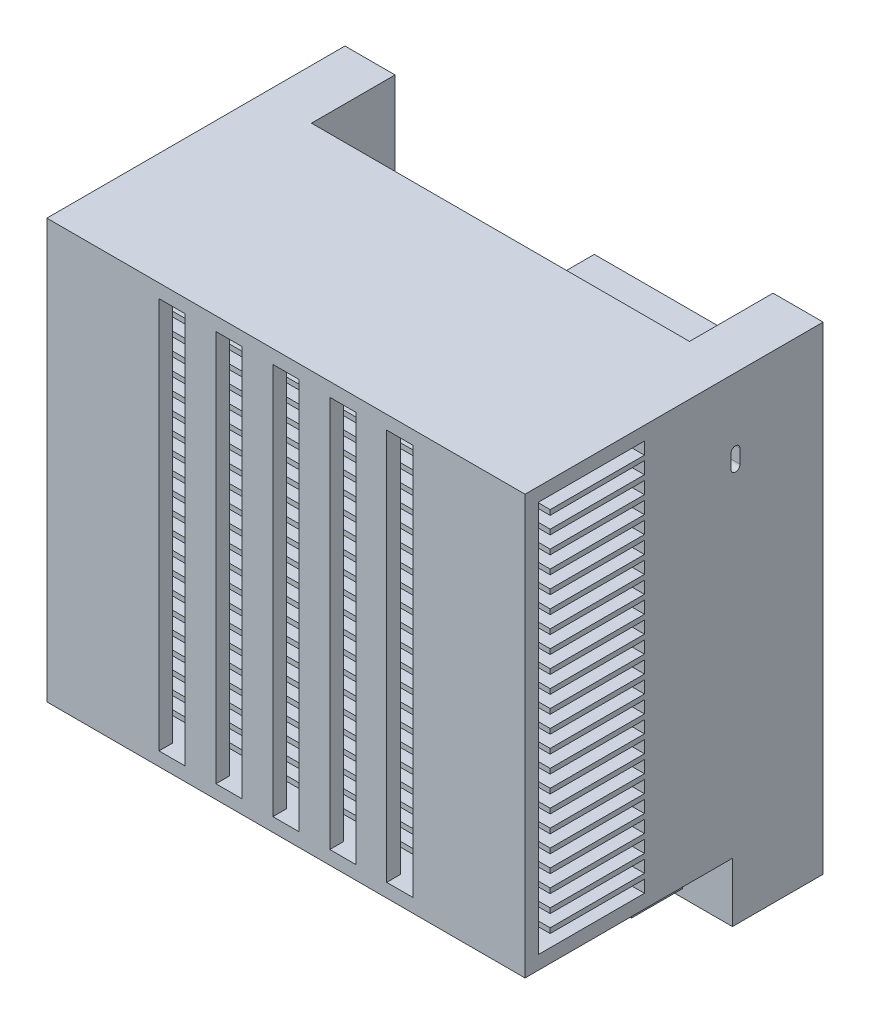
SolidWorks part; units mm, degrees
ref_plane "Plan de face" through (0, 0, 0) normal (0, 0, 1) x (1, 0, 0)
ref_plane "Plan de dessus" through (0, 0, 0) normal (0, 1, 0) x (1, 0, 0)
ref_plane "Plan de droite" through (0, 0, 0) normal (1, 0, 0) x (0, 0, -1)
sketch "Esquisse1" plane through (0, 0, 0) normal (0, 0, 1) x (1, 0, 0)
  line L0 (-52.5, 52.5) -> (-41.5, 52.5)
  line L1 (-52.5, 52.5) -> (-52.5, -52.5)
  line L2 (-52.5, -52.5) -> (-41.5, -52.5)
  line L3 (-41.5, 52.5) -> (-41.5, -52.5)
  line L4 (41.5, 52.5) -> (52.5, 52.5)
  line L5 (41.5, 52.5) -> (41.5, -52.5)
  line L6 (41.5, -52.5) -> (52.5, -52.5)
  line L7 (52.5, 52.5) -> (52.5, -52.5)
  line L8 (-41.5, -52.5) -> (41.5, -52.5) construction
  circle A0 centre (-46, 46) radius 3.2
  circle A1 centre (46, 46) radius 3.2
  circle A2 centre (-46, -33) radius 3.2
  circle A3 centre (46, -33) radius 3.2
  point P16 (-41.5, 0)
  point P19 (0, -52.5)
  dimension "D4" = 6.4
  dimension "D1" = 105
  dimension "D2" = 105
  dimension "D3" = 11
  dimension "D5" = 6.5
  dimension "D6" = 6.5
  dimension "D7" = 6.5
  dimension "D8" = 19.5
extrude "Boss.-Extru.1" add sketch "Esquisse1" along normal blind 18.35
sketch "Esquisse2" plane through (0, 0, 18.35) normal (0, 0, 1) x (1, 0, 0)
  line L1 (-52.5, 52.5) -> (52.5, 52.5)
  line L2 (-52.5, 52.5) -> (-52.5, -52.5)
  line L3 (-52.5, -52.5) -> (52.5, -52.5)
  line L4 (52.5, 52.5) -> (52.5, -52.5)
extrude "Boss.-Extru.2" add sketch "Esquisse2" along normal blind 1.57
sketch "Esquisse3" plane through (0, 0, 19.92) normal (0, 0, 1) x (1, 0, 0)
  line L0 (52.5, -52.5) -> (52.5, 52.5) construction
  line L1 (-52.5, 52.5) -> (52.5, 52.5)
  line L2 (-52.5, 52.5) -> (-52.5, -39.5)
  line L3 (-52.5, -39.5) -> (52.5, -39.5)
  line L4 (52.5, 52.5) -> (52.5, -39.5)
  line L5 (-52.5, -52.5) -> (52.5, -52.5) construction
  dimension "D1" = 13
extrude "Boss.-Extru.3" add sketch "Esquisse3" along normal blind 45.54
sketch "Esquisse4" plane through (0, 0, 19.92) normal (0, 0, 1) x (1, 0, 0)
  line L0 (-47.5, -43.4) -> (41.5, -43.4)
  line L1 (-47.5, -43.4) -> (-47.5, -50.8)
  line L2 (-47.5, -50.8) -> (41.5, -50.8)
  line L3 (41.5, -43.4) -> (41.5, -50.8)
  line L4 (52.5, -52.5) -> (52.5, -39.5) construction
  line L5 (-52.5, -52.5) -> (52.5, -52.5) construction
  dimension "D1" = 7.4
  dimension "D2" = 89
  dimension "D3" = 11
  dimension "D4" = 1.7
extrude "Boss.-Extru.4" add sketch "Esquisse4" along normal blind 11.16
sketch "Esquisse6" plane through (52.5, 0, 0) normal (1, 0, 0) x (0, 0, -1)
  line L0 (-62.46, -36.5) -> (-62.46, 49.5)
  line L1 (-62.46, 49.5) -> (-39.24, 49.5)
  line L2 (-62.46, -36.5) -> (-39.24, -36.5)
  line L3 (-39.24, -36.5) -> (-39.24, -33.81)
  line L4 (-39.24, -33.81) -> (-59.94, -33.81)
  line L5 (-59.94, -33.81) -> (-59.94, -32.71)
  line L6 (-59.94, -32.71) -> (-39.24, -32.71)
  line L7 (-39.24, -32.71) -> (-39.24, -30.02)
  line L8 (-39.24, -30.02) -> (-59.94, -30.02)
  line L9 (-59.94, -30.02) -> (-59.94, -28.92)
  line L10 (-59.94, -28.92) -> (-39.24, -28.92)
  line L11 (-39.24, -28.92) -> (-39.24, -26.23)
  line L12 (-39.24, -26.23) -> (-59.94, -26.23)
  line L13 (-59.94, -26.23) -> (-59.94, -25.13)
  line L14 (-59.94, -25.13) -> (-39.24, -25.13)
  line L15 (-39.24, -25.13) -> (-39.24, -22.44)
  line L16 (-39.24, -22.44) -> (-59.94, -22.44)
  line L17 (-59.94, -22.44) -> (-59.94, -21.34)
  line L18 (-59.94, -21.34) -> (-39.24, -21.34)
  line L19 (-39.24, -21.34) -> (-39.24, -18.65)
  line L20 (-39.24, -18.65) -> (-59.94, -18.65)
  line L21 (-59.94, -18.65) -> (-59.94, -17.55)
  line L22 (-59.94, -17.55) -> (-39.24, -17.55)
  line L23 (-39.24, -17.55) -> (-39.24, -14.86)
  line L24 (-39.24, -14.86) -> (-59.94, -14.86)
  line L25 (-59.94, -14.86) -> (-59.94, -13.76)
  line L26 (-59.94, -13.76) -> (-39.24, -13.76)
  line L27 (-39.24, -13.76) -> (-39.24, -11.07)
  line L28 (-39.24, -11.07) -> (-59.94, -11.07)
  line L29 (-59.94, -11.07) -> (-59.94, -9.97)
  line L30 (-59.94, -9.97) -> (-39.24, -9.97)
  line L31 (-39.24, -9.97) -> (-39.24, -7.28)
  line L32 (-39.24, -7.28) -> (-59.94, -7.28)
  line L33 (-59.94, -7.28) -> (-59.94, -6.18)
  line L34 (-59.94, -6.18) -> (-39.24, -6.18)
  line L35 (-39.24, -6.18) -> (-39.24, -3.49)
  line L36 (-39.24, -3.49) -> (-59.94, -3.49)
  line L37 (-59.94, -3.49) -> (-59.94, -2.39)
  line L38 (-59.94, -2.39) -> (-39.24, -2.39)
  line L39 (-39.24, -2.39) -> (-39.24, 0.3)
  line L40 (-39.24, 0.3) -> (-59.94, 0.3)
  line L41 (-59.94, 0.3) -> (-59.94, 1.4)
  line L42 (-59.94, 1.4) -> (-39.24, 1.4)
  line L43 (-39.24, 1.4) -> (-39.24, 4.09)
  line L44 (-39.24, 4.09) -> (-59.94, 4.09)
  line L45 (-59.94, 4.09) -> (-59.94, 5.19)
  line L46 (-59.94, 5.19) -> (-39.24, 5.19)
  line L47 (-39.24, 5.19) -> (-39.24, 7.88)
  line L48 (-39.24, 7.88) -> (-59.94, 7.88)
  line L49 (-59.94, 7.88) -> (-59.94, 8.98)
  line L50 (-59.94, 8.98) -> (-39.24, 8.98)
  line L51 (-39.24, 8.98) -> (-39.24, 11.67)
  line L52 (-39.24, 11.67) -> (-59.94, 11.67)
  line L53 (-59.94, 11.67) -> (-59.94, 12.77)
  line L54 (-59.94, 12.77) -> (-39.24, 12.77)
  line L55 (-39.24, 12.77) -> (-39.24, 15.46)
  line L56 (-39.24, 15.46) -> (-59.94, 15.46)
  line L57 (-59.94, 15.46) -> (-59.94, 16.56)
  line L58 (-59.94, 16.56) -> (-39.24, 16.56)
  line L59 (-39.24, 16.56) -> (-39.24, 19.25)
  line L60 (-39.24, 19.25) -> (-59.94, 19.25)
  line L61 (-59.94, 19.25) -> (-59.94, 20.35)
  line L62 (-59.94, 20.35) -> (-39.24, 20.35)
  line L63 (-39.24, 20.35) -> (-39.24, 23.04)
  line L64 (-39.24, 23.04) -> (-59.94, 23.04)
  line L65 (-59.94, 23.04) -> (-59.94, 24.14)
  line L66 (-59.94, 24.14) -> (-39.24, 24.14)
  line L67 (-39.24, 24.14) -> (-39.24, 26.83)
  line L68 (-39.24, 26.83) -> (-59.94, 26.83)
  line L69 (-59.94, 26.83) -> (-59.94, 27.93)
  line L70 (-59.94, 27.93) -> (-39.24, 27.93)
  line L71 (-39.24, 27.93) -> (-39.24, 30.62)
  line L72 (-39.24, 30.62) -> (-59.94, 30.62)
  line L73 (-59.94, 30.62) -> (-59.94, 31.72)
  line L74 (-59.94, 31.72) -> (-39.24, 31.72)
  line L75 (-39.24, 31.72) -> (-39.24, 34.41)
  line L76 (-39.24, 34.41) -> (-59.94, 34.41)
  line L77 (-59.94, 34.41) -> (-59.94, 35.51)
  line L78 (-59.94, 35.51) -> (-39.24, 35.51)
  line L79 (-39.24, 35.51) -> (-39.24, 38.2)
  line L80 (-39.24, 38.2) -> (-59.94, 38.2)
  line L81 (-59.94, 38.2) -> (-59.94, 39.3)
  line L82 (-59.94, 39.3) -> (-39.24, 39.3)
  line L83 (-39.24, 39.3) -> (-39.24, 41.99)
  line L84 (-39.24, 41.99) -> (-59.94, 41.99)
  line L85 (-59.94, 41.99) -> (-59.94, 43.09)
  line L86 (-59.94, 43.09) -> (-39.24, 43.09)
  line L87 (-39.24, 43.09) -> (-39.24, 45.78)
  line L88 (-39.24, 45.78) -> (-59.94, 45.71)
  line L89 (-59.94, 45.71) -> (-59.94, 46.81)
  line L90 (-59.94, 46.81) -> (-39.24, 46.81)
  line L91 (-39.24, 49.5) -> (-39.24, 46.81)
  line L92 (-65.46, -39.5) -> (-19.92, -39.5) construction
  line L93 (-65.46, 52.5) -> (0, 52.5) construction
  line L94 (-65.46, -39.5) -> (-65.46, 52.5) construction
  point P96 (-59.94, 27.38)
  point P97 (-39.24, 48.155)
  point P98 (-59.94, 38.75)
  dimension "D1" = 2.52
  dimension "D2" = 2.69
  dimension "D3" = 23.22
  dimension "D4" = 1.1
  dimension "D5" = 3
  dimension "D6" = 3
  dimension "D7" = 3
extrude "Enlèv. mat.-Extru.1" cut sketch "Esquisse6" against normal up to next
sketch "Esquisse7" plane through (0, 0, 65.46) normal (0, 0, 1) x (1, 0, 0)
  line L0 (-52.5, -39.5) -> (52.5, -39.5) construction
  line L1 (22.13, -36.5) -> (27.88, -36.5)
  line L2 (22.13, -36.5) -> (22.13, 49.5)
  line L3 (22.13, 49.5) -> (27.88, 49.5)
  line L4 (27.88, -36.5) -> (27.88, 49.5)
  line L5 (52.5, 52.5) -> (-52.5, 52.5) construction
  line L6 (52.5, -39.5) -> (52.5, 52.5) construction
  line L7 (9.63, -36.5) -> (9.63, 49.5)
  line L8 (9.63, -36.5) -> (15.38, -36.5)
  line L9 (15.38, -36.5) -> (15.38, 49.5)
  line L10 (9.63, 49.5) -> (15.38, 49.5)
  line L11 (-2.87, -36.5) -> (-2.87, 49.5)
  line L12 (-2.87, -36.5) -> (2.88, -36.5)
  line L13 (2.88, -36.5) -> (2.88, 49.5)
  line L14 (-2.87, 49.5) -> (2.88, 49.5)
  line L15 (-15.37, -36.5) -> (-15.37, 49.5)
  line L16 (-15.37, -36.5) -> (-9.62, -36.5)
  line L17 (-9.62, -36.5) -> (-9.62, 49.5)
  line L18 (-15.37, 49.5) -> (-9.62, 49.5)
  line L19 (-27.87, -36.5) -> (-27.87, 49.5)
  line L20 (-27.87, -36.5) -> (-22.12, -36.5)
  line L21 (-22.12, -36.5) -> (-22.12, 49.5)
  line L22 (-27.87, 49.5) -> (-22.12, 49.5)
  dimension "D1" = 3
  dimension "D2" = 3
  dimension "D3" = 24.62
  dimension "D4" = 5.75
  dimension "D5" = 5
extrude "Enlèv. mat.-Extru.2" cut sketch "Esquisse7" against normal up to next contours L14 L11 L12 L13 | L18 L15 L16 L17 | L22 L19 L20 L21 | L2 L1 L4 L3 | L7 L10 L9 L8
sketch "Esquisse8" plane through (0, 0, 18.35) normal (0, 0, -1) x (-1, 0, 0)
  line L0 (-41.5, 52.5) -> (-41.5, -52.5) construction
  line L1 (-40.5, 51.5) -> (-13.5, 51.5)
  line L2 (-40.5, 51.5) -> (-40.5, 43.5)
  line L3 (-40.5, 43.5) -> (-13.5, 43.5)
  line L4 (-13.5, 51.5) -> (-13.5, 43.5)
  line L5 (-41.5, 52.5) -> (41.5, 52.5) construction
  dimension "D1" = 1
  dimension "D2" = 1
  dimension "D3" = 27
  dimension "D4" = 8
extrude "Boss.-Extru.5" add sketch "Esquisse8" along normal blind 7.1
sketch "Esquisse9" plane through (-52.5, 0, 0) normal (-1, 0, 0) x (0, 0, 1)
  line L0 (18.85, 26.5) -> (18.85, 22.626)
  line L1 (18.85, 26.5) -> (12, 26.5)
  line L2 (18.85, 14.5) -> (12, 14.5)
  line L3 (12, 26.5) -> (12, 14.5)
  line L4 (18.85, 22.626) -> (20.53, 22.626)
  line L5 (20.53, 22.626) -> (20.53, 18.374)
  line L6 (20.53, 18.374) -> (18.85, 18.374)
  line L7 (18.85, 18.374) -> (18.85, 14.5)
  line L8 (19.25, 37.6) -> (19.25, 34.6) construction
  line L9 (20.25, 37.6) -> (20.25, 34.6)
  line L10 (18.25, 37.6) -> (18.25, 34.6)
  line L11 (18.85, -13.5) -> (18.85, -27.5)
  line L12 (18.85, -27.5) -> (16.85, -27.5)
  line L13 (16.85, -27.5) -> (16.85, -26.5)
  line L14 (16.85, -26.5) -> (14.85, -23)
  line L15 (14.85, -23) -> (14.85, -18)
  line L16 (14.85, -18) -> (16.85, -14.5)
  line L17 (16.85, -14.5) -> (16.85, -13.5)
  line L18 (16.85, -13.5) -> (18.85, -13.5)
  line L19 (65.46, 52.5) -> (0, 52.5) construction
  line L20 (0, 52.5) -> (0, -52.5) construction
  circle A0 centre (13.25, 36.1) radius 1.25
  circle A1 centre (13.25, 36.1) radius 2.75
  arc A2 (20.25, 37.6) -> (18.25, 37.6) centre (19.25, 37.6) ccw
  arc A3 (18.25, 34.6) -> (20.25, 34.6) centre (19.25, 34.6) ccw
  point P13 (19.25, 36.1)
  point P30 (0, 0)
  point P31 (0, 0)
  point P32 (0, 0)
  point P33 (12.7673, -20.9495)
  dimension "D1" = 2.5
  dimension "D2" = 5.5
  dimension "D13" = 1
  dimension "D3" = 12
  dimension "D4" = 6.85
  dimension "D5" = 1.68
  dimension "D6" = 14
  dimension "D7" = 2
  dimension "D8" = 1
  dimension "D9" = 2
  dimension "D10" = 16.4
  dimension "D11" = 13.25
  dimension "D12" = 3
  dimension "D14" = 6
  dimension "D15" = 26
  dimension "D16" = 5
  dimension "D17" = 66
extrude "Enlèv. mat.-Extru.3" cut sketch "Esquisse9" against normal blind 10
sketch "Esquisse10" plane through (52.5, 0, 0) normal (1, 0, 0) x (0, 0, -1)
  line L2 (-20.25, 34.6) -> (-20.25, 37.6) construction
  line L3 (-18.25, 37.6) -> (-18.25, 34.6) construction
  line L4 (-20.25, 34.6) -> (-20.25, 37.6)
  line L5 (-18.25, 37.6) -> (-18.25, 34.6)
  arc A3 (-20.25, 34.6) -> (-18.25, 34.6) centre (-19.25, 34.6) ccw construction
  arc A4 (-20.25, 34.6) -> (-18.25, 34.6) centre (-19.25, 34.6) ccw
  arc A5 (-18.25, 37.6) -> (-20.25, 37.6) centre (-19.25, 37.6) ccw construction
  arc A6 (-18.25, 37.6) -> (-20.25, 37.6) centre (-19.25, 37.6) ccw
extrude "Enlèv. mat.-Extru.4" cut sketch "Esquisse10" against normal blind 10
